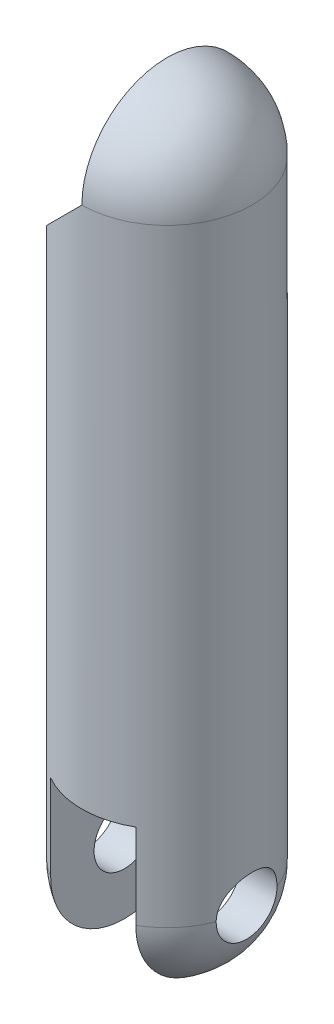
SolidWorks part; units mm, degrees
ref_plane "Front Plane" through (0, 0, 0) normal (0, 0, 1) x (1, 0, 0)
ref_plane "Top Plane" through (0, 0, 0) normal (0, 1, 0) x (1, 0, 0)
ref_plane "Right Plane" through (0, 0, 0) normal (1, 0, 0) x (0, 0, -1)
sketch "Sketch2" plane through (0, 0, 0) normal (0, 1, 0) x (1, 0, 0)
  circle A0 centre (0, 0) radius 70
extrude "Boss-Extrude1" add sketch "Sketch2" along normal blind 500 contours A0
sketch "Sketch3" plane through (0, 0, 0) normal (0, -1, 0) x (-1, 0, 0)
  line L0 (0, 0) -> (0, -70)
  line L1 (0, -70) -> (0, 70)
  arc A0 (0, 70) -> (0, -70) centre (0, 0) ccw
revolve "Revolve1" add sketch "Sketch3" angle 360 about L0
sketch "Sketch4" plane through (0, 500, 0) normal (0, 1, 0) x (1, 0, 0)
  line L0 (0, 70) -> (0, -70)
  arc A0 (0, -70) -> (0, 70) centre (0, 0) ccw
revolve "Revolve2" add sketch "Sketch4" angle 360 about L0
sketch "Sketch5" plane through (0, 0, 0) normal (1, 0, 0) x (0, 0, -1)
  line L0 (0, 77) -> (0, -77) construction
  circle A0 centre (0, 500) radius 70
extrude "Cut-Extrude1" cut sketch "Sketch5" against normal blind 500
sketch "Sketch6" plane through (0, 0, 0) normal (0, 1, 0) x (1, 0, 0)
  line L1 (-35, -70) -> (35, -70)
  line L2 (-35, -70) -> (-35, 70)
  line L3 (-35, 70) -> (35, 70)
  line L4 (35, -70) -> (35, 70)
  line L5 (0, 70) -> (0, -70) construction
  line L6 (-35, 0) -> (35, 0) construction
  point P0 (0, 0)
  dimension "D1" = 70
  dimension "D2" = 140
extrude "Cut-Extrude2" cut sketch "Sketch6" against normal blind 100 and the other way blind 70
sketch "Sketch7" plane through (35, 0, 0) normal (-1, 0, 0) x (0, 0, 1)
  circle A0 centre (0, 0) radius 25
extrude "Cut-Extrude3" cut sketch "Sketch7" against normal blind 100 and the other way blind 120
sketch "Sketch8" plane through (0, 0, 0) normal (-1, 0, 0) x (0, 0, 1)
  circle A0 centre (0, 500) radius 25
extrude "Cut-Extrude4" cut sketch "Sketch8" against normal blind 50
